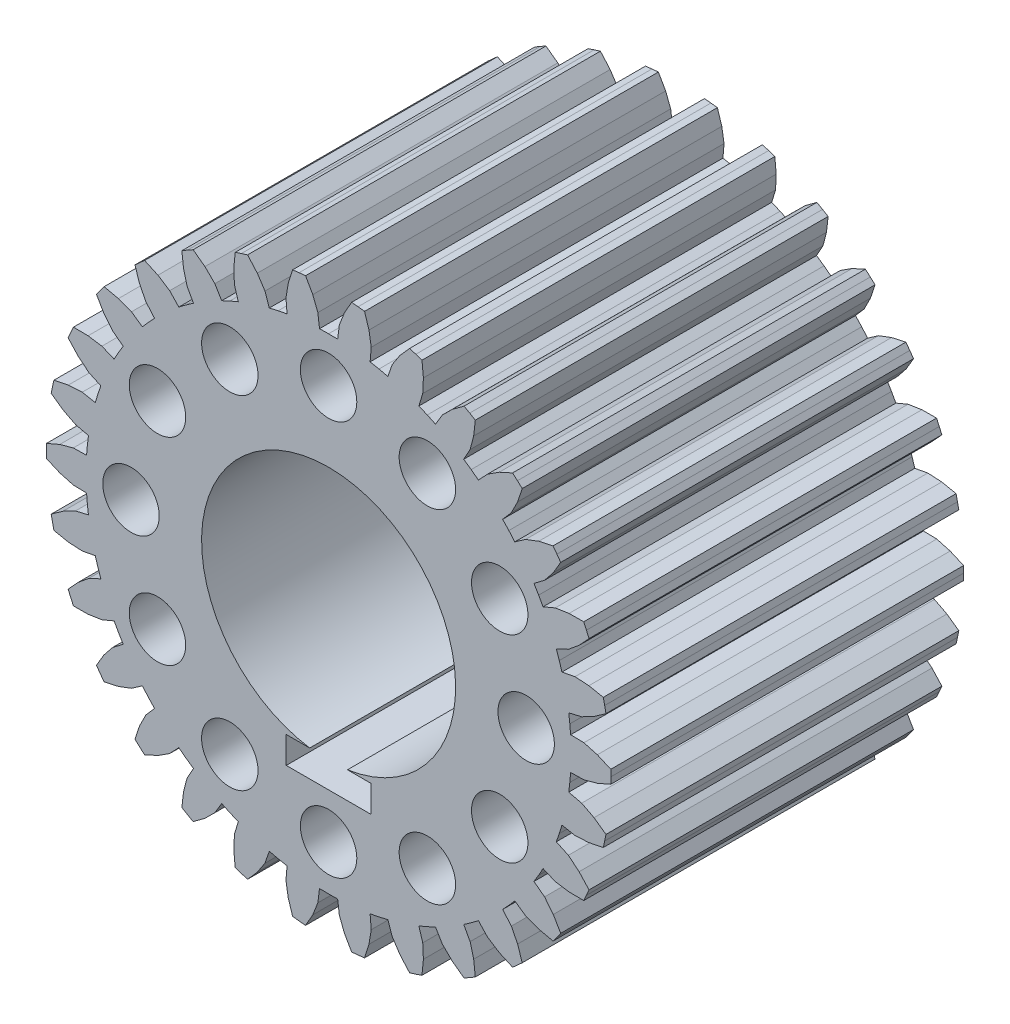
SolidWorks part; units mm, degrees
material "普通碳钢"
ref_plane "前视基准面" through (0, 0, 0) normal (0, 0, 1) x (1, 0, 0)
ref_plane "上视基准面" through (0, 0, 0) normal (0, 1, 0) x (1, 0, 0)
ref_plane "右视基准面" through (0, 0, 0) normal (1, 0, 0) x (0, 0, -1)
other "Configuration Table"
sketch "草图1" plane through (0, 0, 0) normal (0, 0, 1) x (1, 0, 0)
  line L0 (17.1486, -1.1552) -> (18.0893, -1.1364)
  line L1 (18.0893, -1.1364) -> (19.0424, -0.8753)
  line L2 (19.0424, -0.8753) -> (19.9947, -0.4608)
  line L3 (19.9947, -0.4608) -> (20, 0)
  line L4 (20, 0) -> (19.9947, 0.4608)
  line L5 (19.9947, 0.4608) -> (19.0424, 0.8753)
  line L6 (19.0424, 0.8753) -> (18.0893, 1.1364)
  line L7 (18.0893, 1.1364) -> (17.1486, 1.1552)
  line L8 (17.1486, 1.1552) -> (17.0933, 1.7966)
  line L9 (17.0933, 1.7966) -> (17.0141, 2.4354)
  line L10 (17.0141, 2.4354) -> (17.9303, 2.6495)
  line L11 (17.9303, 2.6495) -> (18.8083, 3.103)
  line L12 (18.8083, 3.103) -> (19.6536, 3.7064)
  line L13 (19.6536, 3.7064) -> (19.563, 4.1582)
  line L14 (19.563, 4.1582) -> (19.4619, 4.6079)
  line L15 (19.4619, 4.6079) -> (18.4443, 4.8153)
  line L16 (18.4443, 4.8153) -> (17.4578, 4.8725)
  line L17 (17.4578, 4.8725) -> (16.5337, 4.6954)
  line L18 (16.5337, 4.6954) -> (16.3463, 5.3112)
  line L19 (16.3463, 5.3112) -> (16.1359, 5.9196)
  line L20 (16.1359, 5.9196) -> (16.9876, 6.3195)
  line L21 (16.9876, 6.3195) -> (17.7521, 6.9456)
  line L22 (17.7521, 6.9456) -> (18.4535, 7.7116)
  line L23 (18.4535, 7.7116) -> (18.2709, 8.1347)
  line L24 (18.2709, 8.1347) -> (18.0786, 8.5536)
  line L25 (18.0786, 8.5536) -> (17.0401, 8.5448)
  line L26 (17.0401, 8.5448) -> (16.0632, 8.3957)
  line L27 (16.0632, 8.3957) -> (15.1962, 8.0303)
  line L28 (15.1962, 8.0303) -> (14.8848, 8.5937)
  line L29 (14.8848, 8.5937) -> (14.5526, 9.1451)
  line L30 (14.5526, 9.1451) -> (15.3025, 9.7133)
  line L31 (15.3025, 9.7133) -> (15.9201, 10.4847)
  line L32 (15.9201, 10.4847) -> (16.4469, 11.3798)
  line L33 (16.4469, 11.3798) -> (16.1803, 11.7557)
  line L34 (16.1803, 11.7557) -> (15.9052, 12.1254)
  line L35 (15.9052, 12.1254) -> (14.8911, 11.901)
  line L36 (14.8911, 11.901) -> (13.9666, 11.552)
  line L37 (13.9666, 11.552) -> (13.1945, 11.0143)
  line L38 (13.1945, 11.0143) -> (12.7728, 11.5007)
  line L39 (12.7728, 11.5007) -> (12.3332, 11.9709)
  line L40 (12.3332, 11.9709) -> (12.9486, 12.6826)
  line L41 (12.9486, 12.6826) -> (13.3923, 13.5656)
  line L42 (13.3923, 13.5656) -> (13.7215, 14.5506)
  line L43 (13.7215, 14.5506) -> (13.3826, 14.8629)
  line L44 (13.3826, 14.8629) -> (13.0366, 15.1673)
  line L45 (13.0366, 15.1673) -> (12.0914, 14.7369)
  line L46 (12.0914, 14.7369) -> (11.2596, 14.2034)
  line L47 (11.2596, 14.2034) -> (10.6162, 13.5169)
  line L48 (10.6162, 13.5169) -> (10.1026, 13.905)
  line L49 (10.1026, 13.905) -> (9.5748, 14.2735)
  line L50 (9.5748, 14.2735) -> (10.0288, 15.0976)
  line L51 (10.0288, 15.0976) -> (10.2792, 16.0536)
  line L52 (10.2792, 16.0536) -> (10.3964, 17.0855)
  line L53 (10.3964, 17.0855) -> (10, 17.3205)
  line L54 (10, 17.3205) -> (9.5983, 17.5463)
  line L55 (9.5983, 17.5463) -> (8.7632, 16.9288)
  line L56 (8.7632, 16.9288) -> (8.0606, 16.234)
  line L57 (8.0606, 16.234) -> (7.5739, 15.4288)
  line L58 (7.5739, 15.4288) -> (6.9908, 15.7016)
  line L59 (6.9908, 15.7016) -> (6.3979, 15.9523)
  line L60 (6.3979, 15.9523) -> (6.6707, 16.8528)
  line L61 (6.6707, 16.8528) -> (6.7169, 17.8399)
  line L62 (6.7169, 17.8399) -> (6.617, 18.8737)
  line L63 (6.617, 18.8737) -> (6.1803, 19.0211)
  line L64 (6.1803, 19.0211) -> (5.7404, 19.1585)
  line L65 (5.7404, 19.1585) -> (5.052, 18.3809)
  line L66 (5.052, 18.3809) -> (4.5092, 17.5551)
  line L67 (4.5092, 17.5551) -> (4.2005, 16.6663)
  line L68 (4.2005, 16.6663) -> (3.5735, 16.8119)
  line L69 (3.5735, 16.8119) -> (2.9414, 16.9339)
  line L70 (2.9414, 16.9339) -> (3.021, 17.8715)
  line L71 (3.021, 17.8715) -> (2.861, 18.8466)
  line L72 (2.861, 18.8466) -> (2.5483, 19.837)
  line L73 (2.5483, 19.837) -> (2.0906, 19.8904)
  line L74 (2.0906, 19.8904) -> (1.6317, 19.9333)
  line L75 (1.6317, 19.9333) -> (1.12, 19.0296)
  line L76 (1.12, 19.0296) -> (0.7607, 18.109)
  line L77 (0.7607, 18.109) -> (0.6436, 17.1754)
  line L78 (0.6436, 17.1754) -> (0, 17.1875)
  line L79 (0, 17.1875) -> (-0.6436, 17.1754)
  line L80 (-0.6436, 17.1754) -> (-0.7607, 18.109)
  line L81 (-0.7607, 18.109) -> (-1.12, 19.0296)
  line L82 (-1.12, 19.0296) -> (-1.6317, 19.9333)
  line L83 (-1.6317, 19.9333) -> (-2.0906, 19.8904)
  line L84 (-2.0906, 19.8904) -> (-2.5483, 19.837)
  line L85 (-2.5483, 19.837) -> (-2.861, 18.8466)
  line L86 (-2.861, 18.8466) -> (-3.021, 17.8715)
  line L87 (-3.021, 17.8715) -> (-2.9414, 16.9339)
  line L88 (-2.9414, 16.9339) -> (-3.5735, 16.8119)
  line L89 (-3.5735, 16.8119) -> (-4.2005, 16.6663)
  line L90 (-4.2005, 16.6663) -> (-4.5092, 17.5551)
  line L91 (-4.5092, 17.5551) -> (-5.052, 18.3809)
  line L92 (-5.052, 18.3809) -> (-5.7404, 19.1585)
  line L93 (-5.7404, 19.1585) -> (-6.1803, 19.0211)
  line L94 (-6.1803, 19.0211) -> (-6.617, 18.8737)
  line L95 (-6.617, 18.8737) -> (-6.7169, 17.8399)
  line L96 (-6.7169, 17.8399) -> (-6.6707, 16.8528)
  line L97 (-6.6707, 16.8528) -> (-6.3979, 15.9523)
  line L98 (-6.3979, 15.9523) -> (-6.9908, 15.7016)
  line L99 (-6.9908, 15.7016) -> (-7.5739, 15.4288)
  line L100 (-7.5739, 15.4288) -> (-8.0606, 16.234)
  line L101 (-8.0606, 16.234) -> (-8.7632, 16.9288)
  line L102 (-8.7632, 16.9288) -> (-9.5983, 17.5463)
  line L103 (-9.5983, 17.5463) -> (-10, 17.3205)
  line L104 (-10, 17.3205) -> (-10.3964, 17.0855)
  line L105 (-10.3964, 17.0855) -> (-10.2792, 16.0536)
  line L106 (-10.2792, 16.0536) -> (-10.0288, 15.0976)
  line L107 (-10.0288, 15.0976) -> (-9.5748, 14.2735)
  line L108 (-9.5748, 14.2735) -> (-10.1026, 13.905)
  line L109 (-10.1026, 13.905) -> (-10.6162, 13.5169)
  line L110 (-10.6162, 13.5169) -> (-11.2596, 14.2034)
  line L111 (-11.2596, 14.2034) -> (-12.0914, 14.7369)
  line L112 (-12.0914, 14.7369) -> (-13.0366, 15.1673)
  line L113 (-13.0366, 15.1673) -> (-13.3826, 14.8629)
  line L114 (-13.3826, 14.8629) -> (-13.7215, 14.5506)
  line L115 (-13.7215, 14.5506) -> (-13.3923, 13.5656)
  line L116 (-13.3923, 13.5656) -> (-12.9486, 12.6826)
  line L117 (-12.9486, 12.6826) -> (-12.3332, 11.9709)
  line L118 (-12.3332, 11.9709) -> (-12.7728, 11.5007)
  line L119 (-12.7728, 11.5007) -> (-13.1945, 11.0143)
  line L120 (-13.1945, 11.0143) -> (-13.9666, 11.552)
  line L121 (-13.9666, 11.552) -> (-14.8911, 11.901)
  line L122 (-14.8911, 11.901) -> (-15.9052, 12.1254)
  line L123 (-15.9052, 12.1254) -> (-16.1803, 11.7557)
  line L124 (-16.1803, 11.7557) -> (-16.4469, 11.3798)
  line L125 (-16.4469, 11.3798) -> (-15.9201, 10.4847)
  line L126 (-15.9201, 10.4847) -> (-15.3025, 9.7133)
  line L127 (-15.3025, 9.7133) -> (-14.5526, 9.1451)
  line L128 (-14.5526, 9.1451) -> (-14.8848, 8.5938)
  line L129 (-14.8848, 8.5938) -> (-15.1962, 8.0303)
  line L130 (-15.1962, 8.0303) -> (-16.0632, 8.3957)
  line L131 (-16.0632, 8.3957) -> (-17.0401, 8.5448)
  line L132 (-17.0401, 8.5448) -> (-18.0786, 8.5536)
  line L133 (-18.0786, 8.5536) -> (-18.2709, 8.1347)
  line L134 (-18.2709, 8.1347) -> (-18.4535, 7.7116)
  line L135 (-18.4535, 7.7116) -> (-17.7521, 6.9456)
  line L136 (-17.7521, 6.9456) -> (-16.9876, 6.3195)
  line L137 (-16.9876, 6.3195) -> (-16.1359, 5.9196)
  line L138 (-16.1359, 5.9196) -> (-16.3463, 5.3112)
  line L139 (-16.3463, 5.3112) -> (-16.5337, 4.6954)
  line L140 (-16.5337, 4.6954) -> (-17.4578, 4.8725)
  line L141 (-17.4578, 4.8725) -> (-18.4443, 4.8153)
  line L142 (-18.4443, 4.8153) -> (-19.4619, 4.6079)
  line L143 (-19.4619, 4.6079) -> (-19.563, 4.1582)
  line L144 (-19.563, 4.1582) -> (-19.6536, 3.7064)
  line L145 (-19.6536, 3.7064) -> (-18.8083, 3.103)
  line L146 (-18.8083, 3.103) -> (-17.9303, 2.6495)
  line L147 (-17.9303, 2.6495) -> (-17.0141, 2.4354)
  line L148 (-17.0141, 2.4354) -> (-17.0933, 1.7966)
  line L149 (-17.0933, 1.7966) -> (-17.1486, 1.1552)
  line L150 (-17.1486, 1.1552) -> (-18.0893, 1.1364)
  line L151 (-18.0893, 1.1364) -> (-19.0424, 0.8753)
  line L152 (-19.0424, 0.8753) -> (-19.9947, 0.4608)
  line L153 (-19.9947, 0.4608) -> (-20, 0)
  line L154 (-20, 0) -> (-19.9947, -0.4608)
  line L155 (-19.9947, -0.4608) -> (-19.0424, -0.8753)
  line L156 (-19.0424, -0.8753) -> (-18.0893, -1.1364)
  line L157 (-18.0893, -1.1364) -> (-17.1486, -1.1552)
  line L158 (-17.1486, -1.1552) -> (-17.0933, -1.7966)
  line L159 (-17.0933, -1.7966) -> (-17.0141, -2.4354)
  line L160 (-17.0141, -2.4354) -> (-17.9303, -2.6495)
  line L161 (-17.9303, -2.6495) -> (-18.8083, -3.103)
  line L162 (-18.8083, -3.103) -> (-19.6536, -3.7064)
  line L163 (-19.6536, -3.7064) -> (-19.563, -4.1582)
  line L164 (-19.563, -4.1582) -> (-19.4619, -4.6079)
  line L165 (-19.4619, -4.6079) -> (-18.4443, -4.8153)
  line L166 (-18.4443, -4.8153) -> (-17.4578, -4.8725)
  line L167 (-17.4578, -4.8725) -> (-16.5337, -4.6954)
  line L168 (-16.5337, -4.6954) -> (-16.3463, -5.3112)
  line L169 (-16.3463, -5.3112) -> (-16.1359, -5.9196)
  line L170 (-16.1359, -5.9196) -> (-16.9876, -6.3195)
  line L171 (-16.9876, -6.3195) -> (-17.7521, -6.9456)
  line L172 (-17.7521, -6.9456) -> (-18.4535, -7.7116)
  line L173 (-18.4535, -7.7116) -> (-18.2709, -8.1347)
  line L174 (-18.2709, -8.1347) -> (-18.0786, -8.5536)
  line L175 (-18.0786, -8.5536) -> (-17.0401, -8.5448)
  line L176 (-17.0401, -8.5448) -> (-16.0632, -8.3957)
  line L177 (-16.0632, -8.3957) -> (-15.1962, -8.0303)
  line L178 (-15.1962, -8.0303) -> (-14.8848, -8.5937)
  line L179 (-14.8848, -8.5937) -> (-14.5526, -9.1451)
  line L180 (-14.5526, -9.1451) -> (-15.3025, -9.7133)
  line L181 (-15.3025, -9.7133) -> (-15.9201, -10.4847)
  line L182 (-15.9201, -10.4847) -> (-16.4469, -11.3798)
  line L183 (-16.4469, -11.3798) -> (-16.1803, -11.7557)
  line L184 (-16.1803, -11.7557) -> (-15.9052, -12.1254)
  line L185 (-15.9052, -12.1254) -> (-14.8911, -11.901)
  line L186 (-14.8911, -11.901) -> (-13.9666, -11.552)
  line L187 (-13.9666, -11.552) -> (-13.1945, -11.0143)
  line L188 (-13.1945, -11.0143) -> (-12.7728, -11.5007)
  line L189 (-12.7728, -11.5007) -> (-12.3332, -11.9709)
  line L190 (-12.3332, -11.9709) -> (-12.9486, -12.6826)
  line L191 (-12.9486, -12.6826) -> (-13.3923, -13.5656)
  line L192 (-13.3923, -13.5656) -> (-13.7215, -14.5506)
  line L193 (-13.7215, -14.5506) -> (-13.3826, -14.8629)
  line L194 (-13.3826, -14.8629) -> (-13.0366, -15.1673)
  line L195 (-13.0366, -15.1673) -> (-12.0914, -14.7369)
  line L196 (-12.0914, -14.7369) -> (-11.2596, -14.2034)
  line L197 (-11.2596, -14.2034) -> (-10.6162, -13.5169)
  line L198 (-10.6162, -13.5169) -> (-10.1026, -13.905)
  line L199 (-10.1026, -13.905) -> (-9.5748, -14.2735)
  line L200 (-9.5748, -14.2735) -> (-10.0288, -15.0976)
  line L201 (-10.0288, -15.0976) -> (-10.2792, -16.0536)
  line L202 (-10.2792, -16.0536) -> (-10.3964, -17.0855)
  line L203 (-10.3964, -17.0855) -> (-10, -17.3205)
  line L204 (-10, -17.3205) -> (-9.5983, -17.5463)
  line L205 (-9.5983, -17.5463) -> (-8.7632, -16.9288)
  line L206 (-8.7632, -16.9288) -> (-8.0606, -16.234)
  line L207 (-8.0606, -16.234) -> (-7.5739, -15.4288)
  line L208 (-7.5739, -15.4288) -> (-6.9908, -15.7016)
  line L209 (-6.9908, -15.7016) -> (-6.3979, -15.9523)
  line L210 (-6.3979, -15.9523) -> (-6.6707, -16.8528)
  line L211 (-6.6707, -16.8528) -> (-6.7169, -17.8399)
  line L212 (-6.7169, -17.8399) -> (-6.617, -18.8737)
  line L213 (-6.617, -18.8737) -> (-6.1803, -19.0211)
  line L214 (-6.1803, -19.0211) -> (-5.7404, -19.1585)
  line L215 (-5.7404, -19.1585) -> (-5.052, -18.3809)
  line L216 (-5.052, -18.3809) -> (-4.5092, -17.5551)
  line L217 (-4.5092, -17.5551) -> (-4.2005, -16.6663)
  line L218 (-4.2005, -16.6663) -> (-3.5735, -16.8119)
  line L219 (-3.5735, -16.8119) -> (-2.9414, -16.9339)
  line L220 (-2.9414, -16.9339) -> (-3.021, -17.8715)
  line L221 (-3.021, -17.8715) -> (-2.861, -18.8466)
  line L222 (-2.861, -18.8466) -> (-2.5483, -19.837)
  line L223 (-2.5483, -19.837) -> (-2.0906, -19.8904)
  line L224 (-2.0906, -19.8904) -> (-1.6317, -19.9333)
  line L225 (-1.6317, -19.9333) -> (-1.12, -19.0296)
  line L226 (-1.12, -19.0296) -> (-0.7607, -18.109)
  line L227 (-0.7607, -18.109) -> (-0.6436, -17.1754)
  line L228 (-0.6436, -17.1754) -> (0, -17.1875)
  line L229 (0, -17.1875) -> (0.6436, -17.1754)
  line L230 (0.6436, -17.1754) -> (0.7607, -18.109)
  line L231 (0.7607, -18.109) -> (1.12, -19.0296)
  line L232 (1.12, -19.0296) -> (1.6317, -19.9333)
  line L233 (1.6317, -19.9333) -> (2.0906, -19.8904)
  line L234 (2.0906, -19.8904) -> (2.5483, -19.837)
  line L235 (2.5483, -19.837) -> (2.861, -18.8466)
  line L236 (2.861, -18.8466) -> (3.021, -17.8715)
  line L237 (3.021, -17.8715) -> (2.9414, -16.9339)
  line L238 (2.9414, -16.9339) -> (3.5735, -16.8119)
  line L239 (3.5735, -16.8119) -> (4.2005, -16.6663)
  line L240 (4.2005, -16.6663) -> (4.5092, -17.5551)
  line L241 (4.5092, -17.5551) -> (5.052, -18.3809)
  line L242 (5.052, -18.3809) -> (5.7404, -19.1585)
  line L243 (5.7404, -19.1585) -> (6.1803, -19.0211)
  line L244 (6.1803, -19.0211) -> (6.617, -18.8737)
  line L245 (6.617, -18.8737) -> (6.7169, -17.8399)
  line L246 (6.7169, -17.8399) -> (6.6707, -16.8528)
  line L247 (6.6707, -16.8528) -> (6.3979, -15.9523)
  line L248 (6.3979, -15.9523) -> (6.9908, -15.7016)
  line L249 (6.9908, -15.7016) -> (7.5739, -15.4288)
  line L250 (7.5739, -15.4288) -> (8.0606, -16.234)
  line L251 (8.0606, -16.234) -> (8.7632, -16.9288)
  line L252 (8.7632, -16.9288) -> (9.5983, -17.5463)
  line L253 (9.5983, -17.5463) -> (10, -17.3205)
  line L254 (10, -17.3205) -> (10.3964, -17.0855)
  line L255 (10.3964, -17.0855) -> (10.2792, -16.0536)
  line L256 (10.2792, -16.0536) -> (10.0288, -15.0976)
  line L257 (10.0288, -15.0976) -> (9.5748, -14.2735)
  line L258 (9.5748, -14.2735) -> (10.1026, -13.905)
  line L259 (10.1026, -13.905) -> (10.6162, -13.5169)
  line L260 (10.6162, -13.5169) -> (11.2596, -14.2034)
  line L261 (11.2596, -14.2034) -> (12.0914, -14.7369)
  line L262 (12.0914, -14.7369) -> (13.0366, -15.1673)
  line L263 (13.0366, -15.1673) -> (13.3826, -14.8629)
  line L264 (13.3826, -14.8629) -> (13.7215, -14.5506)
  line L265 (13.7215, -14.5506) -> (13.3923, -13.5656)
  line L266 (13.3923, -13.5656) -> (12.9486, -12.6826)
  line L267 (12.9486, -12.6826) -> (12.3332, -11.9709)
  line L268 (12.3332, -11.9709) -> (12.7728, -11.5007)
  line L269 (12.7728, -11.5007) -> (13.1945, -11.0143)
  line L270 (13.1945, -11.0143) -> (13.9666, -11.552)
  line L271 (13.9666, -11.552) -> (14.8911, -11.901)
  line L272 (14.8911, -11.901) -> (15.9052, -12.1254)
  line L273 (15.9052, -12.1254) -> (16.1803, -11.7557)
  line L274 (16.1803, -11.7557) -> (16.4469, -11.3798)
  line L275 (16.4469, -11.3798) -> (15.9201, -10.4847)
  line L276 (15.9201, -10.4847) -> (15.3025, -9.7133)
  line L277 (15.3025, -9.7133) -> (14.5526, -9.1451)
  line L278 (14.5526, -9.1451) -> (14.8848, -8.5937)
  line L279 (14.8848, -8.5937) -> (15.1962, -8.0303)
  line L280 (15.1962, -8.0303) -> (16.0632, -8.3957)
  line L281 (16.0632, -8.3957) -> (17.0401, -8.5448)
  line L282 (17.0401, -8.5448) -> (18.0786, -8.5536)
  line L283 (18.0786, -8.5536) -> (18.2709, -8.1347)
  line L284 (18.2709, -8.1347) -> (18.4535, -7.7116)
  line L285 (18.4535, -7.7116) -> (17.7521, -6.9456)
  line L286 (17.7521, -6.9456) -> (16.9876, -6.3195)
  line L287 (16.9876, -6.3195) -> (16.1359, -5.9196)
  line L288 (16.1359, -5.9196) -> (16.3463, -5.3112)
  line L289 (16.3463, -5.3112) -> (16.5337, -4.6954)
  line L290 (16.5337, -4.6954) -> (17.4578, -4.8725)
  line L291 (17.4578, -4.8725) -> (18.4443, -4.8153)
  line L292 (18.4443, -4.8153) -> (19.4619, -4.6079)
  line L293 (19.4619, -4.6079) -> (19.563, -4.1582)
  line L294 (19.563, -4.1582) -> (19.6536, -3.7064)
  line L295 (19.6536, -3.7064) -> (18.8083, -3.103)
  line L296 (18.8083, -3.103) -> (17.9303, -2.6495)
  line L297 (17.9303, -2.6495) -> (17.0141, -2.4354)
  line L298 (17.0141, -2.4354) -> (17.0933, -1.7966)
  line L299 (17.0933, -1.7966) -> (17.1486, -1.1552)
  circle A0 centre (0, 0) radius 9
extrude "01_GEAR_BODY" add sketch "草图1" along normal blind 25
sketch "草图2" plane through (0, 0, 0) normal (0, 0, 1) x (1, 0, 0)
  circle A0 centre (0, 14) radius 2
  circle A1 centre (-7, 12.1244) radius 2
  circle A2 centre (-12.1244, 7) radius 2
  circle A3 centre (-14, 0) radius 2
  circle A4 centre (-12.1244, -7) radius 2
  circle A5 centre (-7, -12.1244) radius 2
  circle A6 centre (0, -14) radius 2
  circle A7 centre (7, -12.1244) radius 2
  circle A8 centre (12.1244, -7) radius 2
  circle A9 centre (14, 0) radius 2
  circle A10 centre (12.1244, 7) radius 2
  circle A11 centre (7, 12.1244) radius 2
extrude "02_HOLES_12" cut sketch "草图2" along normal through all
sketch "草图3" plane through (0, 0, 0) normal (0, 0, 1) x (1, 0, 0)
  line L1 (-3, -10.8) -> (3, -10.8)
  line L2 (-3, -10.8) -> (-3, -8.9)
  line L3 (-3, -8.9) -> (3, -8.9)
  line L4 (3, -10.8) -> (3, -8.9)
extrude "03_KEYWAY" cut sketch "草图3" along normal through all
